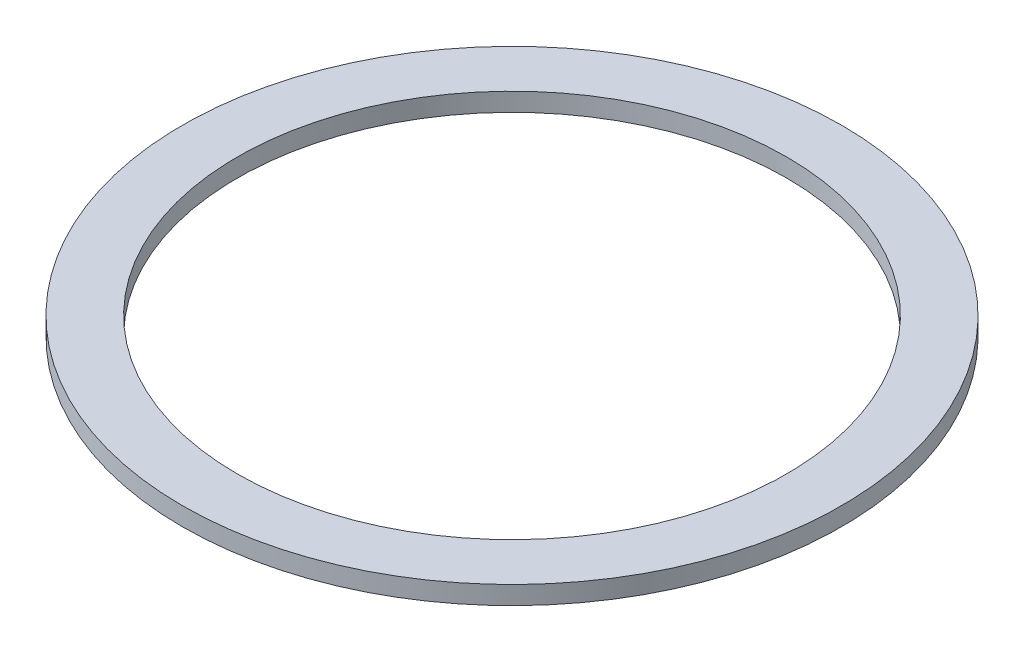
SolidWorks part; units mm, degrees
ref_plane "Front Plane" through (0, 0, 0) normal (0, 0, 1) x (1, 0, 0)
ref_plane "Top Plane" through (0, 0, 0) normal (0, 1, 0) x (1, 0, 0)
ref_plane "Right Plane" through (0, 0, 0) normal (1, 0, 0) x (0, 0, -1)
sketch "Sketch1" plane through (0, 0, 0) normal (0, 1, 0) x (1, 0, 0)
  circle A0 centre (0, 0) radius 150
  circle A1 centre (0, 0) radius 180
  dimension "D1" = 300
  dimension "D2" = 360
extrude "Boss-Extrude1" add sketch "Sketch1" along normal mid plane 10
